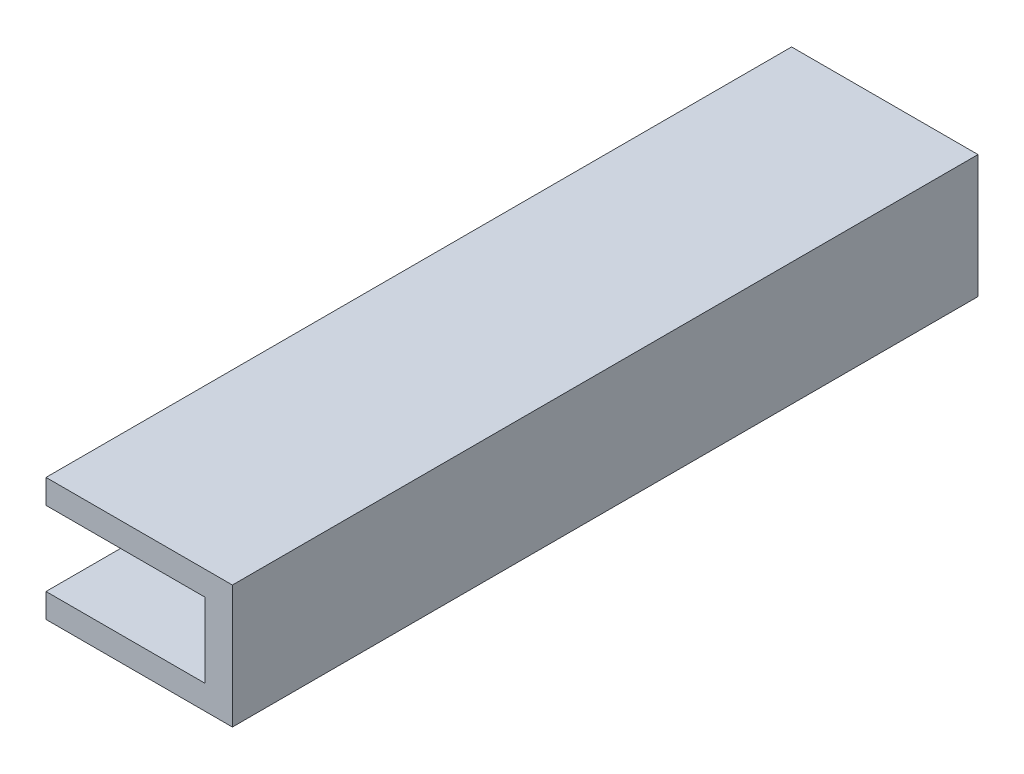
SolidWorks part; units mm, degrees
ref_plane "Plan de face" through (0, 0, 0) normal (0, 0, 1) x (1, 0, 0)
ref_plane "Plan de dessus" through (0, 0, 0) normal (0, 1, 0) x (1, 0, 0)
ref_plane "Plan de droite" through (0, 0, 0) normal (1, 0, 0) x (0, 0, -1)
sketch "Esquisse1" plane through (0, 0, 0) normal (0, 0, 1) x (1, 0, 0)
  line L0 (-50, 26.5) -> (-7.3267, 26.5)
  line L1 (-50, 33) -> (0, 33)
  line L2 (-50, 33) -> (-50, 26.5)
  line L3 (-50, 0) -> (0, 0)
  line L4 (0, 33) -> (0, 0)
  line L5 (-7.3267, 26.5) -> (-7.3267, 6.5)
  line L6 (-7.3267, 6.5) -> (-50, 6.5)
  line L7 (-50, 6.5) -> (-50, 0)
  point P8 (-7.3267, 6.5)
  dimension "D1" = 50
  dimension "D2" = 33
  dimension "D3" = 20
extrude "Boss.-Extru.1" add sketch "Esquisse1" along normal blind 200
